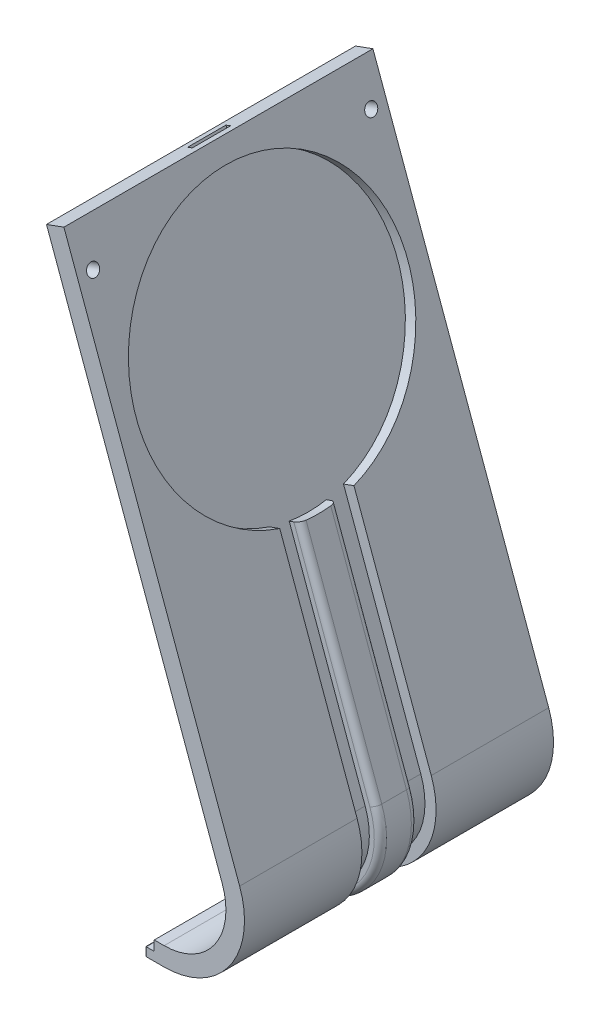
SolidWorks part; units mm, degrees
material "PLA"
ref_plane "前视基准面" through (0, 0, 0) normal (0, 0, 1) x (1, 0, 0)
ref_plane "上视基准面" through (0, 0, 0) normal (0, 1, 0) x (1, 0, 0)
ref_plane "右视基准面" through (0, 0, 0) normal (1, 0, 0) x (0, 0, -1)
other "Configuration Table"
sketch "草图2" plane through (0, 0, 0) normal (0, 0, 1) x (1, 0, 0)
  line L5 (40.0883, 20.3249) -> (11.6565, 98.4406)
  line L7 (13.6945, 105.2907) -> (9.3719, 103.7174) construction
  line L8 (9.3719, 104.7174) -> (40.3995, 19.4699) construction
  line L9 (40.0883, 20.3249) -> (40.5581, 20.4959) construction
  line L10 (30.6913, 6.9047) -> (30.6913, 6.4047) construction
  line L12 (30.6913, 6.9047) -> (29.0913, 6.9047)
  line L13 (-41.9715, 6.9047) -> (30.6913, 6.9047) construction
  arc A0 (30.6913, 6.9047) -> (40.0883, 20.3249) centre (30.6913, 16.9047) ccw
  arc A4 (30.6913, 6.9047) -> (40.0883, 20.3249) centre (30.6913, 16.9047) ccw construction
  point P4 (40.0886, 20.3239)
  point P5 (40.1728, 20.0831)
  point P7 (0, 0)
  point P16 (40.0883, 20.3249)
  point P18 (31.8444, 6.0437)
  point P19 (33.2018, 6.1547)
  point P20 (30.6913, 6.9047)
  point P25 (30.0867, 6.9047)
  dimension "D2" = 1.6
  dimension "D1" = 5.74
extrude "整体拉伸-薄壁1" add sketch "草图2" along normal mid plane 50 thin
sketch "草图4" plane through (44.7502, 16.2877, 0) normal (0.9397, 0.342, 0) x (0, 0, -1)
  line L0 (-25, 88.5171) -> (25, 88.5171) construction
  circle A0 centre (0, 63.1171) radius 22
  dimension "D1" = 44
  dimension "D2" = 25.4
extrude "中间圆切除-拉伸1" cut sketch "草图4" against normal blind 1.8
sketch "草图3" plane through (0, 0, 0) normal (0, 0, 1) x (1, 0, 0)
  line L0 (42.9073, 21.351) -> (14.4756, 99.4666) construction
  line L1 (42.9073, 21.351) -> (14.4756, 99.4666) construction
  line L2 (29.0913, 3.9047) -> (29.0913, 6.9047) construction
  line L5 (41.2159, 20.7354) -> (28.9959, 54.3095)
  line L6 (41.2159, 20.7354) -> (12.7841, 98.851) construction
  line L7 (29.0913, 5.8196) -> (29.0913, 5.8196) construction
  line L9 (28.9959, 54.3095) -> (30.6873, 54.9252) construction
  line L16 (28.9959, 54.3095) -> (27.9698, 57.1286)
  line L17 (27.2941, 5.9192) -> (20.0759, 9.4006) construction
  arc A0 (30.6913, 6.9047) -> (40.0883, 20.3249) centre (30.6913, 16.9047) ccw construction
  arc A1 (20.0759, 9.4006) -> (42.9073, 21.351) centre (30.6913, 16.9047) ccw construction
  arc A2 (29.0913, 5.8196) -> (41.2159, 20.7354) centre (30.6913, 16.9047) ccw
  dimension "D2" = 3
  dimension "D1" = 1.8
extrude "线槽切除-拉伸-薄壁1" cut sketch "草图3" against normal blind 3 from offset 6 thin
mirror "镜向1" about plane through (0, 0, 0) normal (0, 0, 1) of "线槽切除-拉伸-薄壁1"
sketch "草图11" plane through (29.0913, 0, 0) normal (-1, 0, 0) x (0, 0, 1)
  line L0 (-25, 3.9047) -> (-25, 6.9047) construction
  line L1 (-25, 5.3047) -> (-6, 5.3047)
  line L2 (-25, 5.3047) -> (-25, 3.9047)
  line L3 (-25, 3.9047) -> (-6, 3.9047)
  line L4 (-6, 5.3047) -> (-6, 3.9047)
  line L5 (-6, 5.8196) -> (-6, 4.0036) construction
  line L6 (6, 5.3047) -> (25, 5.3047)
  line L7 (6, 5.3047) -> (6, 3.9047)
  line L8 (6, 3.9047) -> (25, 3.9047)
  line L9 (25, 5.3047) -> (25, 3.9047)
  line L10 (25, 3.9047) -> (-25, 3.9047) construction
  line L11 (6, 4.0036) -> (6, 5.8196) construction
  line L12 (25, 3.9047) -> (25, 6.9047) construction
  line L14 (25, 6.9047) -> (-25, 6.9047) construction
  dimension "D1" = 1.6
  dimension "D2" = 1.6
extrude "底部卡扣凸台-拉伸3" add sketch "草图11" along normal blind 1.5
fillet "底部卡扣圆角1" radius 0.25 8 edges at (27.5913, 5.3047, 15.5) (27.5913, 4.6047, 25) (27.5913, 3.9047, 15.5) (27.5913, 4.6047, 6) (27.5913, 5.3047, -15.5) (27.5913, 4.6047, -6) (27.5913, 3.9047, -15.5) (27.5913, 4.6047, -25)
sketch "草图14" plane through (-30.2746, 83.1789, 0) normal (-0.342, 0.9397, 0) x (0.9397, 0.342, 0)
  line L0 (44.2802, -5.1) -> (47.2802, -5.1) construction
  line L1 (46.4222, 3.1) -> (45.6222, 3.1)
  line L2 (46.4222, 3.1) -> (46.4222, -3.1)
  line L3 (46.4222, -3.1) -> (45.6222, -3.1)
  line L4 (45.6222, 3.1) -> (45.6222, -3.1)
  line L5 (47.2802, 5.1) -> (44.2802, 5.1) construction
  line L6 (44.6222, -25) -> (44.6222, 25) construction
  line L7 (47.6222, -25) -> (47.6222, 25) construction
  dimension "D1" = 2
  dimension "D2" = 2
  dimension "D3" = 1
  dimension "D4" = 1.2
extrude "扣部切除-拉伸2" cut sketch "草图14" against normal blind 1
sketch "草图15" plane through (0, 3.9047, 0) normal (0, -1, 0) x (1, 0, 0)
  line L0 (30.6913, 6) -> (43.6913, 6) construction
  line L1 (27.8413, 6) -> (30.6913, 6)
  line L2 (27.8413, 6) -> (27.8413, -6)
  line L3 (27.8413, -6) -> (30.6913, -6)
  line L4 (30.6913, 6) -> (30.6913, -6)
  line L5 (43.6913, -6) -> (30.6913, -6) construction
  line L6 (30.6913, -3) -> (30.6913, -6) construction
  line L7 (27.8413, 25) -> (27.8413, 6) construction
extrude "切除-拉伸1" cut sketch "草图15" against normal up to surface (1.8 mm away)
fillet "圆角1" radius 1 5 edges at (36.7622, 38.2346, 3) (36.7622, 38.2346, -3) (30.6913, 3.9047, 0) (41.3403, 9.4482, 3) (41.3403, 9.4482, -3)
sketch "草图16" plane through (41.9311, 15.2617, 0) normal (-0.9397, -0.342, 0) x (0, 0, 1)
  line L0 (0, 88.5171) -> (0, 76.6011) construction
  line L1 (25, 88.5171) -> (-25, 88.5171) construction
  line L2 (-25, 5.3882) -> (-25, 88.5171) construction
  circle A0 centre (-22.5, 82.0171) radius 1
  circle A1 centre (22.5, 82.0171) radius 1
  dimension "D1" = 2
  dimension "D2" = 6.5
  dimension "D3" = 2.5
extrude "切除-拉伸2" cut sketch "草图16" against normal up to next
